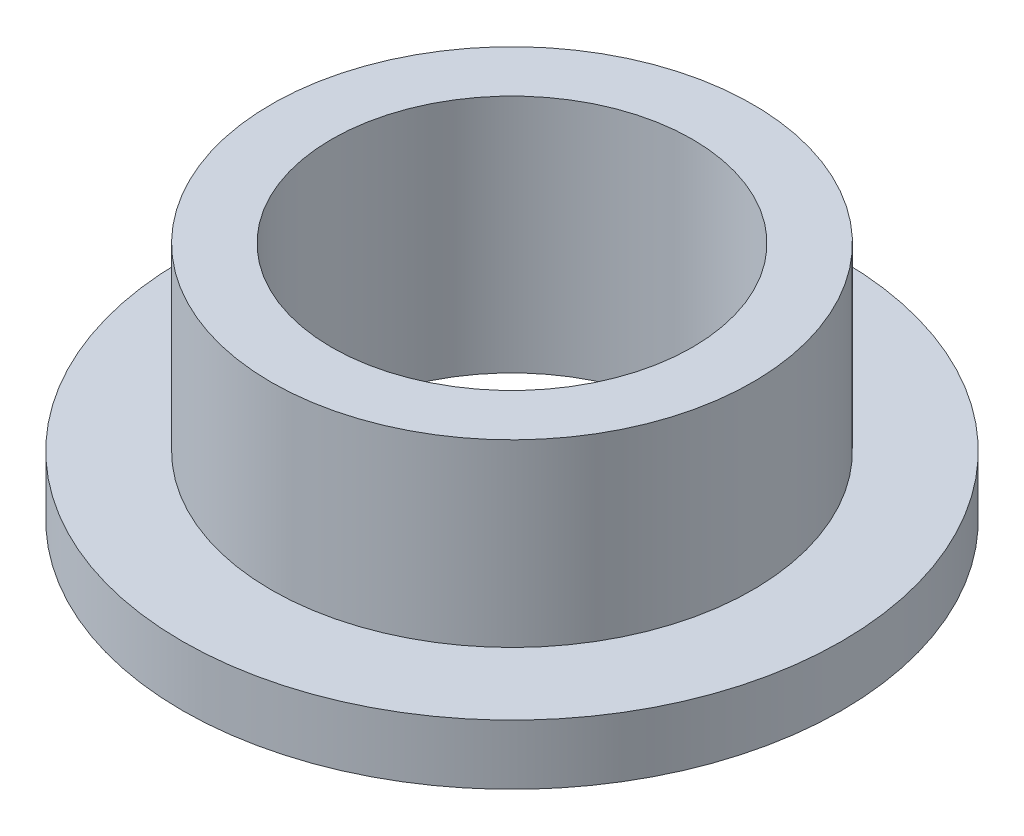
SolidWorks part; units mm, degrees
ref_plane "Front" through (0, 0, 0) normal (0, 0, 1) x (1, 0, 0)
ref_plane "Top" through (0, 0, 0) normal (0, 1, 0) x (1, 0, 0)
ref_plane "Right" through (0, 0, 0) normal (1, 0, 0) x (0, 0, -1)
sketch "Sketch1" plane through (0, 0, 0) normal (0, 1, 0) x (1, 0, 0)
  circle A0 centre (0, 0) radius 4.7752
  circle A1 centre (0, 0) radius 6.3754
  circle A2 centre (0, 0) radius 8.7312
  dimension "ID" = 9.5504
  dimension "OD" = 12.7508
  dimension "FlangeOD" = 17.4625
sketch "Sketch2" plane through (0, 0, 0) normal (0, 1, 0) x (1, 0, 0)
  circle A0 centre (0, 0) radius 4.7752 construction
  circle A1 centre (0, 0) radius 6.3754 construction
  circle A2 centre (0, 0) radius 4.7752
  circle A3 centre (0, 0) radius 6.3754
extrude "Boss-Extrude1" add sketch "Sketch2" along normal blind 6.35
sketch "Sketch3" plane through (0, 0, 0) normal (0, 1, 0) x (1, 0, 0)
  circle A0 centre (0, 0) radius 8.7312 construction
  circle A1 centre (0, 0) radius 6.3754 construction
  circle A2 centre (0, 0) radius 8.7312
  circle A3 centre (0, 0) radius 6.3754
extrude "Boss-Extrude2" add sketch "Sketch3" along normal blind 1.5875
